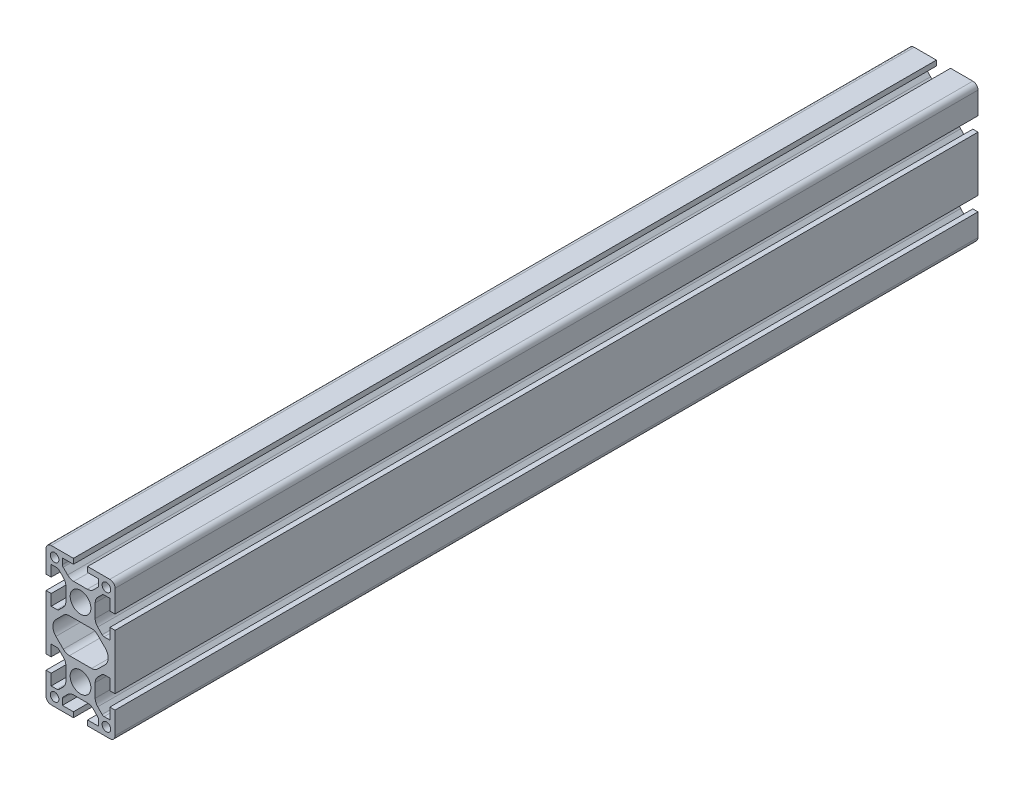
SolidWorks part; units mm, degrees
ref_plane "Front Plane" through (0, 0, 0) normal (0, 0, 1) x (1, 0, 0)
ref_plane "Top Plane" through (0, 0, 0) normal (0, 1, 0) x (1, 0, 0)
ref_plane "Right Plane" through (0, 0, 0) normal (1, 0, 0) x (0, 0, -1)
sketch "Sketch1" plane through (0, 0, 0) normal (0, 0, 1) x (1, 0, 0)
  line L0 (-17, -40) -> (-4.1, -40)
  line L1 (-4.1, -40) -> (-4.1, -37)
  line L2 (-4.1, -37) -> (-10.5, -37)
  line L3 (-10.5, -37) -> (-10.5, -33.6627)
  line L4 (-10.0314, -32.5314) -> (-7.4645, -29.9645)
  line L5 (-3.9289, -28.5) -> (3.9289, -28.5)
  line L6 (7.4645, -29.9645) -> (10.0314, -32.5314)
  line L7 (10.5, -33.6627) -> (10.5, -37)
  line L8 (10.5, -37) -> (4.1, -37)
  line L9 (4.1, -37) -> (4.1, -40)
  line L10 (4.1, -40) -> (17, -40)
  line L11 (20, -37) -> (20, -24.1)
  line L12 (20, -24.1) -> (17, -24.1)
  line L13 (17, -24.1) -> (17, -30.5)
  line L14 (17, -30.5) -> (13.6627, -30.5)
  line L15 (12.5314, -30.0314) -> (9.9645, -27.4645)
  line L16 (8.5, -23.9289) -> (8.5, -16.0711)
  line L17 (9.9645, -12.5355) -> (12.5314, -9.9686)
  line L18 (13.6627, -9.5) -> (17, -9.5)
  line L19 (17, -9.5) -> (17, -15.9)
  line L20 (17, -15.9) -> (20, -15.9)
  line L21 (20, -15.9) -> (20, 15.9)
  line L22 (20, 15.9) -> (17, 15.9)
  line L23 (17, 15.9) -> (17, 9.5)
  line L24 (17, 9.5) -> (13.6627, 9.5)
  line L25 (12.5314, 9.9686) -> (9.9645, 12.5355)
  line L26 (8.5, 16.0711) -> (8.5, 23.9289)
  line L27 (9.9645, 27.4645) -> (12.5314, 30.0314)
  line L28 (13.6627, 30.5) -> (17, 30.5)
  line L29 (17, 30.5) -> (17, 24.1)
  line L30 (17, 24.1) -> (20, 24.1)
  line L31 (20, 24.1) -> (20, 37)
  line L32 (17, 40) -> (4.1, 40)
  line L33 (4.1, 40) -> (4.1, 37)
  line L34 (4.1, 37) -> (10.5, 37)
  line L35 (10.5, 37) -> (10.5, 33.6627)
  line L36 (10.0314, 32.5314) -> (7.4645, 29.9645)
  line L37 (3.9289, 28.5) -> (-3.9289, 28.5)
  line L38 (-7.4645, 29.9645) -> (-10.0314, 32.5314)
  line L39 (-10.5, 33.6627) -> (-10.5, 37)
  line L40 (-10.5, 37) -> (-4.1, 37)
  line L41 (-4.1, 37) -> (-4.1, 40)
  line L42 (-4.1, 40) -> (-17, 40)
  line L43 (-20, 37) -> (-20, 24.1)
  line L44 (-20, 24.1) -> (-17, 24.1)
  line L45 (-17, 24.1) -> (-17, 30.5)
  line L46 (-17, 30.5) -> (-13.6627, 30.5)
  line L47 (-12.5314, 30.0314) -> (-9.9645, 27.4645)
  line L48 (-8.5, 23.9289) -> (-8.5, 16.0711)
  line L49 (-9.9645, 12.5355) -> (-12.5314, 9.9686)
  line L50 (-13.6627, 9.5) -> (-17, 9.5)
  line L51 (-17, 9.5) -> (-17, 15.9)
  line L52 (-17, 15.9) -> (-20, 15.9)
  line L53 (-20, 15.9) -> (-20, -15.9)
  line L54 (-20, -15.9) -> (-17, -15.9)
  line L55 (-17, -15.9) -> (-17, -9.5)
  line L56 (-17, -9.5) -> (-13.6627, -9.5)
  line L57 (-12.5314, -9.9686) -> (-9.9645, -12.5355)
  line L58 (-8.5, -16.0711) -> (-8.5, -23.9289)
  line L59 (-9.9645, -27.4645) -> (-12.5314, -30.0314)
  line L60 (-13.6627, -30.5) -> (-17, -30.5)
  line L61 (-17, -30.5) -> (-17, -24.1)
  line L62 (-17, -24.1) -> (-20, -24.1)
  line L63 (-20, -24.1) -> (-20, -37)
  line L64 (-14.2426, -4.2426) -> (-9.9497, -8.5355)
  line L65 (-6.4142, -10) -> (6.4142, -10)
  line L66 (9.9497, -8.5355) -> (14.2426, -4.2426)
  line L67 (14.2426, 4.2426) -> (9.9497, 8.5355)
  line L68 (6.4142, 10) -> (-6.4142, 10)
  line L69 (-9.9497, 8.5355) -> (-14.2426, 4.2426)
  arc A0 (-20, -37) -> (-17, -40) centre (-17, -37) ccw
  arc A1 (-10.5, -33.6627) -> (-10.0314, -32.5314) centre (-8.9, -33.6627) cw
  arc A2 (-7.4645, -29.9645) -> (-3.9289, -28.5) centre (-3.9289, -33.5) cw
  arc A3 (3.9289, -28.5) -> (7.4645, -29.9645) centre (3.9289, -33.5) cw
  arc A4 (10.0314, -32.5314) -> (10.5, -33.6627) centre (8.9, -33.6627) cw
  arc A5 (17, -40) -> (20, -37) centre (17, -37) ccw
  arc A6 (13.6627, -30.5) -> (12.5314, -30.0314) centre (13.6627, -28.9) cw
  arc A7 (9.9645, -27.4645) -> (8.5, -23.9289) centre (13.5, -23.9289) cw
  arc A8 (8.5, -16.0711) -> (9.9645, -12.5355) centre (13.5, -16.0711) cw
  arc A9 (12.5314, -9.9686) -> (13.6627, -9.5) centre (13.6627, -11.1) cw
  arc A10 (13.6627, 9.5) -> (12.5314, 9.9686) centre (13.6627, 11.1) cw
  arc A11 (9.9645, 12.5355) -> (8.5, 16.0711) centre (13.5, 16.0711) cw
  arc A12 (8.5, 23.9289) -> (9.9645, 27.4645) centre (13.5, 23.9289) cw
  arc A13 (12.5314, 30.0314) -> (13.6627, 30.5) centre (13.6627, 28.9) cw
  arc A14 (20, 37) -> (17, 40) centre (17, 37) ccw
  arc A15 (10.5, 33.6627) -> (10.0314, 32.5314) centre (8.9, 33.6627) cw
  arc A16 (7.4645, 29.9645) -> (3.9289, 28.5) centre (3.9289, 33.5) cw
  arc A17 (-3.9289, 28.5) -> (-7.4645, 29.9645) centre (-3.9289, 33.5) cw
  arc A18 (-10.0314, 32.5314) -> (-10.5, 33.6627) centre (-8.9, 33.6627) cw
  arc A19 (-17, 40) -> (-20, 37) centre (-17, 37) ccw
  arc A20 (-13.6627, 30.5) -> (-12.5314, 30.0314) centre (-13.6627, 28.9) cw
  arc A21 (-9.9645, 27.4645) -> (-8.5, 23.9289) centre (-13.5, 23.9289) cw
  arc A22 (-8.5, 16.0711) -> (-9.9645, 12.5355) centre (-13.5, 16.0711) cw
  arc A23 (-12.5314, 9.9686) -> (-13.6627, 9.5) centre (-13.6627, 11.1) cw
  arc A24 (-13.6627, -9.5) -> (-12.5314, -9.9686) centre (-13.6627, -11.1) cw
  arc A25 (-9.9645, -12.5355) -> (-8.5, -16.0711) centre (-13.5, -16.0711) cw
  arc A26 (-8.5, -23.9289) -> (-9.9645, -27.4645) centre (-13.5, -23.9289) cw
  arc A27 (-12.5314, -30.0314) -> (-13.6627, -30.5) centre (-13.6627, -28.9) cw
  circle A28 centre (15, 35) radius 2.5
  circle A29 centre (15, -35) radius 2.5
  circle A30 centre (0, 20) radius 6
  circle A31 centre (0, -20) radius 6
  arc A32 (-14.2426, 4.2426) -> (-14.2426, -4.2426) centre (-10, 0) ccw
  arc A33 (-9.9497, -8.5355) -> (-6.4142, -10) centre (-6.4142, -5) ccw
  arc A34 (6.4142, -10) -> (9.9497, -8.5355) centre (6.4142, -5) ccw
  arc A35 (14.2426, -4.2426) -> (14.2426, 4.2426) centre (10, 0) ccw
  arc A36 (9.9497, 8.5355) -> (6.4142, 10) centre (6.4142, 5) ccw
  arc A37 (-6.4142, 10) -> (-9.9497, 8.5355) centre (-6.4142, 5) ccw
  circle A38 centre (-15, 35) radius 2.5
  circle A39 centre (-15, -35) radius 2.5
  dimension "D1" = 40
  dimension "D2" = 80
extrude "Boss-Extrude1" add sketch "Sketch1" against normal blind 500
